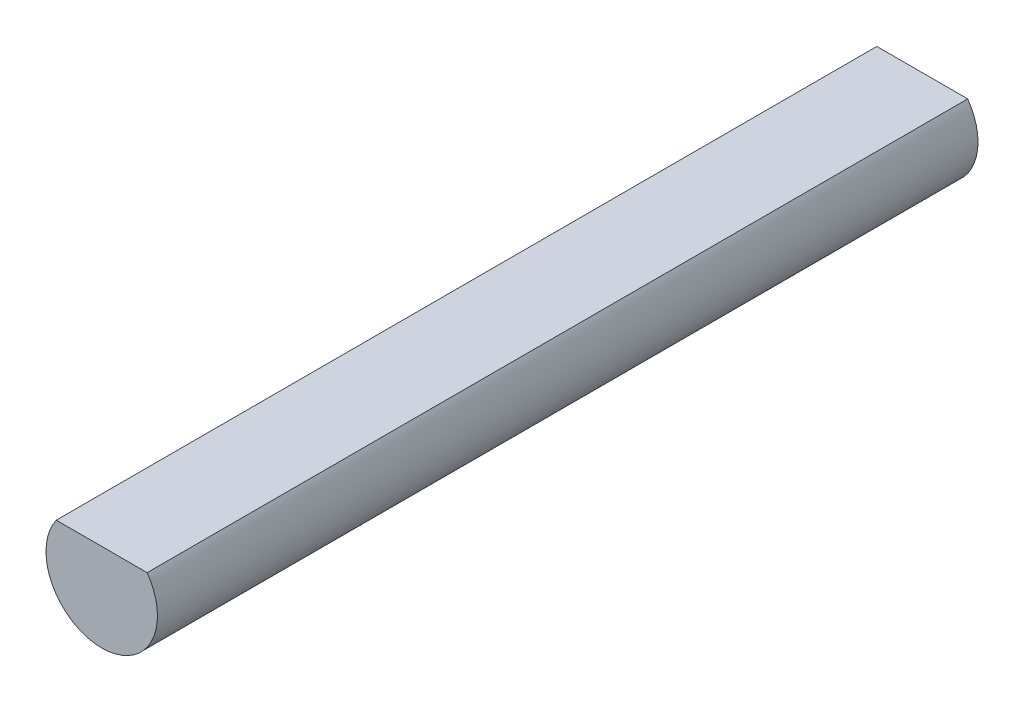
SolidWorks part; units mm, degrees
ref_plane "Front Plane" through (0, 0, 0) normal (0, 0, 1) x (1, 0, 0)
ref_plane "Top Plane" through (0, 0, 0) normal (0, 1, 0) x (1, 0, 0)
ref_plane "Right Plane" through (0, 0, 0) normal (1, 0, 0) x (0, 0, -1)
sketch "Sketch1" plane through (0, 0, 0) normal (0, 0, 1) x (1, 0, 0)
  circle A0 centre (0, 0) radius 3.1369
  dimension "D1" = 6.2738
extrude "Boss-Extrude1" add sketch "Sketch1" against normal blind 46.1899
sketch "Sketch2" plane through (0, 0, 0) normal (0, 0, 1) x (1, 0, 0)
  line L0 (-3.1369, 0) -> (3.1369, 0) construction
  line L2 (-2.5577, 1.8161) -> (2.5577, 1.8161)
  arc A0 (-2.5577, 1.8161) -> (2.5577, 1.8161) centre (0, 0) cw
  circle A1 centre (0, 0) radius 3.1369 construction
  dimension "D2" = 1.8161
extrude "Cut-Extrude1" cut sketch "Sketch2" against normal through all contours A0 L2
